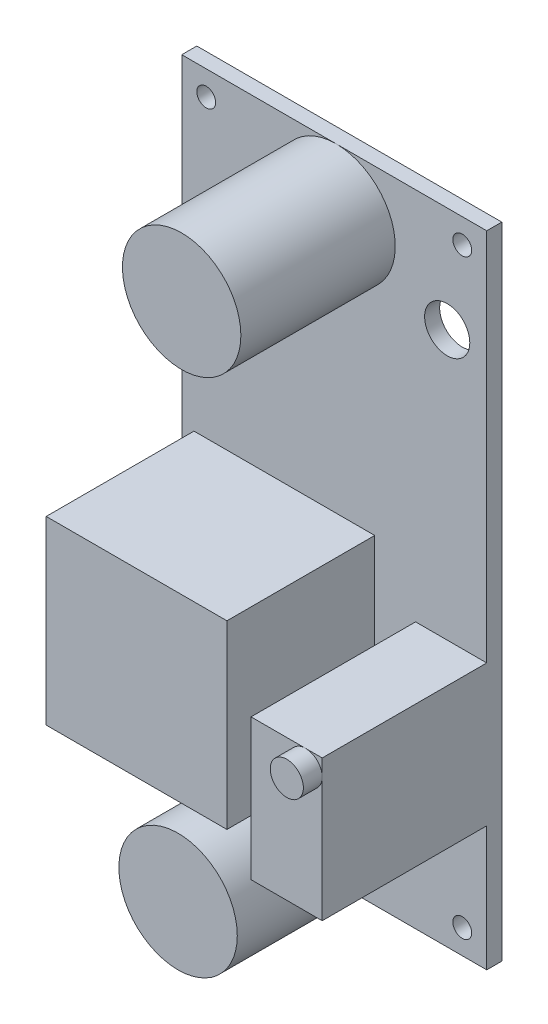
SolidWorks part; units mm, degrees
ref_plane "Front Plane" through (0, 0, 0) normal (0, 0, 1) x (1, 0, 0)
ref_plane "Top Plane" through (0, 0, 0) normal (0, 1, 0) x (1, 0, 0)
ref_plane "Right Plane" through (0, 0, 0) normal (1, 0, 0) x (0, 0, -1)
sketch "Sketch1" plane through (0, 0, 0) normal (0, 0, 1) x (1, 0, 0)
  line L1 (0, 43.18) -> (20.574, 43.18)
  line L2 (0, 43.18) -> (0, 0)
  line L3 (0, 0) -> (20.574, 0)
  line L4 (20.574, 43.18) -> (20.574, 0)
  dimension "D1" = 43.18
  dimension "D2" = 20.574
extrude "Boss-Extrude1" add sketch "Sketch1" along normal blind 1.016
sketch "Sketch2" plane through (0, 0, 1.016) normal (0, 0, 1) x (1, 0, 0)
  line L0 (17.907, 36.068) -> (20.574, 36.068) construction
  line L1 (17.907, 43.18) -> (17.907, 36.068) construction
  line L2 (0, 6.35) -> (3.0988, 6.35) construction
  line L3 (3.0988, 0) -> (3.0988, 6.35) construction
  line L4 (0, 0) -> (20.574, 0) construction
  line L5 (0, 43.18) -> (0, 0) construction
  line L6 (20.574, 0) -> (20.574, 43.18) construction
  line L7 (20.574, 43.18) -> (0, 43.18) construction
  circle A0 centre (17.907, 36.068) radius 1.524
  circle A1 centre (3.0988, 6.35) radius 1.524
  dimension "D5" = 3.048
  dimension "D1" = 7.112
  dimension "D2" = 6.35
  dimension "D3" = 2.667
  dimension "D4" = 3.0988
extrude "Cut-Extrude1" cut sketch "Sketch2" against normal through all
sketch "Sketch3" plane through (0, 0, 1.016) normal (0, 0, 1) x (1, 0, 0)
  line L0 (18.923, 43.18) -> (18.923, 41.529) construction
  line L1 (18.923, 41.529) -> (20.574, 41.529) construction
  line L2 (1.651, 43.18) -> (1.651, 41.529) construction
  line L3 (0, 41.529) -> (1.651, 41.529) construction
  line L4 (1.651, 0) -> (1.651, 1.651) construction
  line L5 (0, 1.651) -> (1.651, 1.651) construction
  line L6 (18.923, 1.651) -> (18.923, 0) construction
  line L7 (20.574, 1.651) -> (18.923, 1.651) construction
  line L8 (20.574, 43.18) -> (0, 43.18) construction
  line L9 (0, 43.18) -> (0, 0) construction
  line L10 (20.574, 0) -> (20.574, 43.18) construction
  line L11 (0, 0) -> (20.574, 0) construction
  circle A0 centre (18.923, 41.529) radius 0.635
  circle A1 centre (18.923, 1.651) radius 0.635
  circle A2 centre (1.651, 1.651) radius 0.635
  circle A3 centre (1.651, 41.529) radius 0.635
  dimension "D1" = 1.27
  dimension "D2" = 1.651
extrude "Cut-Extrude2" cut sketch "Sketch3" against normal blind 2.54
sketch "Sketch4" plane through (0, 0, 0) normal (0, 0, -1) x (-1, 0, 0)
  line L0 (-17.4213, 43.18) -> (-17.4213, 40.386) construction
  line L1 (-17.4213, 0) -> (-17.4213, 3.9936) construction
  line L2 (0, 40.386) -> (-20.574, 40.386) construction
  line L3 (0, 43.18) -> (0, 0) construction
  line L4 (-20.574, 43.18) -> (0, 43.18) construction
  line L6 (-2.4416, 43.18) -> (-2.4416, 40.386) construction
  line L7 (-2.4416, 0) -> (-2.4416, 3.9936) construction
  line L8 (-20.574, 0) -> (-20.574, 43.18) construction
  line L9 (0, 0) -> (-20.574, 0) construction
  line L10 (0, 3.9936) -> (-20.574, 3.9936) construction
  line L11 (0, 43.18) -> (0, 0) construction
  text T0 "IN+" font "Century Gothic" height in points 3
  text T1 "IN-" font "Century Gothic" height in points 3
  text T2 "OUT+" font "Century Gothic" height in points 3
  text T3 "OUT-" font "Century Gothic" height in points 3
  dimension "D1" = 3.9936
  dimension "D2" = 2.794
extrude "Boss-Extrude2" add sketch "Sketch4" along normal blind 0.0025
sketch "Sketch5" plane through (0, 0, 1.016) normal (0, 0, 1) x (1, 0, 0)
  line L0 (0, 15.5067) -> (0.8255, 15.5067) construction
  line L1 (0.8255, 21.6027) -> (13.0175, 21.6027)
  line L2 (0.8255, 21.6027) -> (0.8255, 9.4107)
  line L3 (0.8255, 9.4107) -> (13.0175, 9.4107)
  line L4 (13.0175, 21.6027) -> (13.0175, 9.4107)
  line L5 (6.9215, 9.4107) -> (6.9215, 0) construction
  line L6 (0, 0) -> (20.574, 0) construction
  line L7 (20.574, 0) -> (20.574, 43.18) construction
  line L9 (0, 43.18) -> (0, 0) construction
  dimension "D1" = 12.192
  dimension "D2" = 0.8255
  dimension "D3" = 9.4107
extrude "Boss-Extrude3" add sketch "Sketch5" along normal blind 9.9695
sketch "Sketch6" plane through (0, 0, 1.016) normal (0, 0, 1) x (1, 0, 0)
  line L0 (10.1664, 3.9942) -> (20.574, 3.9942) construction
  line L1 (10.4076, 43.18) -> (10.4076, 39.1858) construction
  line L2 (0, 39.1858) -> (10.4076, 39.1858) construction
  line L3 (20.574, 43.18) -> (0, 43.18) construction
  line L4 (0, 43.18) -> (0, 0) construction
  line L5 (10.1664, 3.9942) -> (10.1664, 0) construction
  line L7 (0, 0) -> (20.574, 0) construction
  line L8 (20.574, 0) -> (20.574, 43.18) construction
  circle A0 centre (10.4076, 39.1858) radius 3.9942
  circle A1 centre (10.1664, 3.9942) radius 3.9941
  dimension "D1" = 7.9883
  dimension "D2" = 3.9942
  dimension "D3" = 10.4076
extrude "Boss-Extrude4" add sketch "Sketch6" along normal blind 10.414
sketch "Sketch7" plane through (0, 0, 1.016) normal (0, 0, 1) x (1, 0, 0)
  line L0 (0, 43.18) -> (0, 0) construction
  line L1 (15.7734, 17.9324) -> (20.574, 17.9324)
  line L2 (15.7734, 17.9324) -> (15.7734, 8.4201)
  line L3 (15.7734, 8.4201) -> (20.574, 8.4201)
  line L4 (20.574, 17.9324) -> (20.574, 8.4201)
  line L5 (10.4076, 43.18) -> (0, 43.18) construction
  line L6 (20.574, 8.4201) -> (20.574, 0) construction
  line L7 (20.574, 0) -> (20.574, 43.18) construction
  dimension "D1" = 4.8006
  dimension "D2" = 9.5123
  dimension "D3" = 8.4201
extrude "Boss-Extrude5" add sketch "Sketch7" along normal blind 11.0998
sketch "Sketch8" plane through (0, 0, 12.1158) normal (0, 0, 1) x (1, 0, 0)
  line L0 (20.574, 16.8148) -> (19.4564, 16.8148) construction
  line L1 (19.4564, 17.9324) -> (19.4564, 16.8148) construction
  line L2 (20.574, 17.9324) -> (15.7734, 17.9324) construction
  line L3 (20.574, 8.4201) -> (20.574, 17.9324) construction
  circle A0 centre (19.4564, 16.8148) radius 1.1176
  dimension "D1" = 2.2352
  dimension "D2" = 1.1176
  dimension "D3" = 1.1176
extrude "Boss-Extrude6" add sketch "Sketch8" along normal blind 1.27
